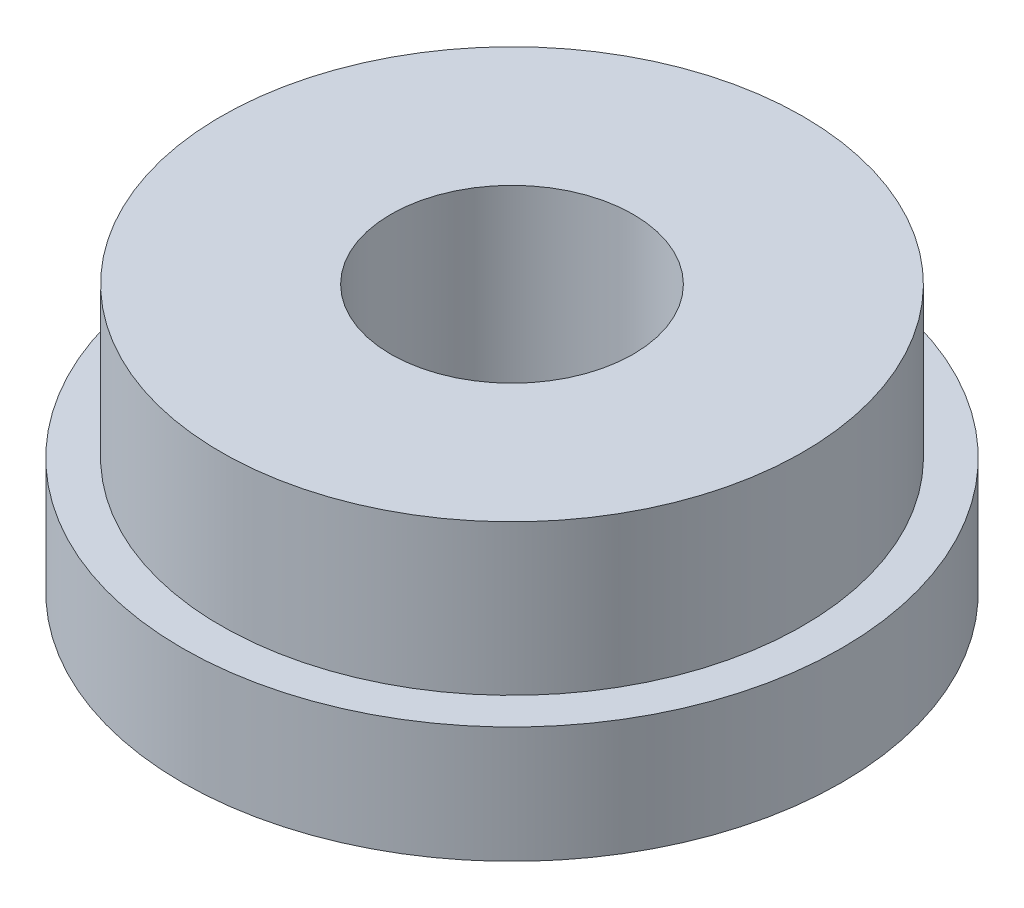
SolidWorks part; units mm, degrees
material "ｱﾙﾐ青銅"
ref_plane "正面" through (0, 0, 0) normal (0, 0, 1) x (1, 0, 0)
ref_plane "平面" through (0, 0, 0) normal (0, 1, 0) x (1, 0, 0)
ref_plane "右側面" through (0, 0, 0) normal (1, 0, 0) x (0, 0, -1)
sketch "ｽｹｯﾁ1" plane through (0, 0, 0) normal (0, 0, 1) x (1, 0, 0)
  line L0 (1.25, 0) -> (1.25, 2.75)
  line L1 (1.25, 2.75) -> (3, 2.75)
  line L2 (3, 2.75) -> (3, 1.2)
  line L3 (3, 1.2) -> (3.4, 1.2)
  line L4 (3.4, 1.2) -> (3.4, 0)
  line L5 (3.4, 0) -> (1.25, 0)
  line L6 (0, 0) -> (0, 2.75) construction
  dimension "D1" = 2.75
  dimension "D2" = 1.2
  dimension "D3" = 3.4
  dimension "D4" = 3
  dimension "D5" = 1.25
revolve "回転1" add sketch "ｽｹｯﾁ1" angle 360 about L6
